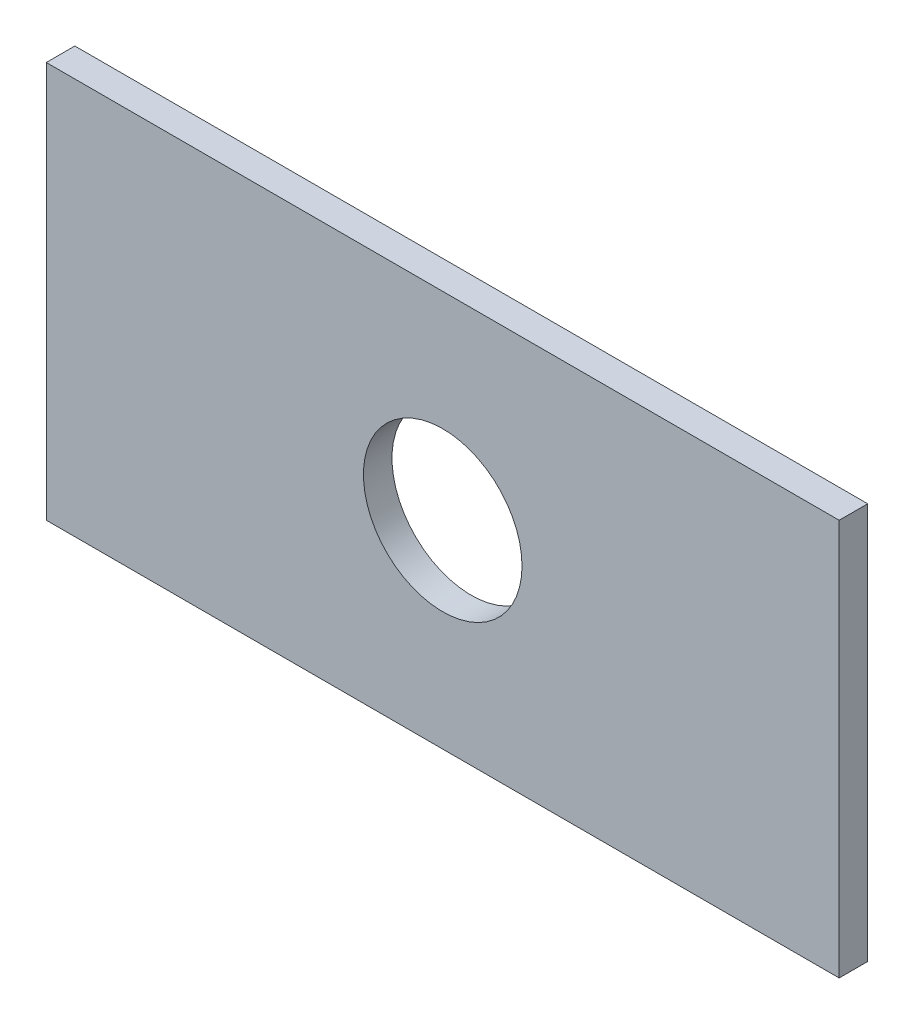
SolidWorks part; units mm, degrees
ref_plane "Plano frontal" through (0, 0, 0) normal (0, 0, 1) x (1, 0, 0)
ref_plane "Plano superior" through (0, 0, 0) normal (0, 1, 0) x (1, 0, 0)
ref_plane "Plano direito" through (0, 0, 0) normal (1, 0, 0) x (0, 0, -1)
sketch "Esboço1" plane through (0, 0, 0) normal (0, 0, 1) x (1, 0, 0)
  line L1 (25, 12.5) -> (-25, 12.5)
  line L2 (25, 12.5) -> (25, -12.5)
  line L3 (25, -12.5) -> (-25, -12.5)
  line L4 (-25, 12.5) -> (-25, -12.5)
  line L5 (25, 12.5) -> (-25, -12.5) construction
  line L6 (25, -12.5) -> (-25, 12.5) construction
  point P0 (0, 0)
  dimension "D1" = 25
  dimension "D2" = 50
extrude "Ressalto-extrusão1" add sketch "Esboço1" along normal blind 1.8
sketch "Esboço2" plane through (0, 0, 1.8) normal (0, 0, 1) x (1, 0, 0)
  circle A0 centre (0, 0) radius 5
  dimension "D1" = 10
extrude "Corte-extrusão1" cut sketch "Esboço2" against normal blind 1.8
